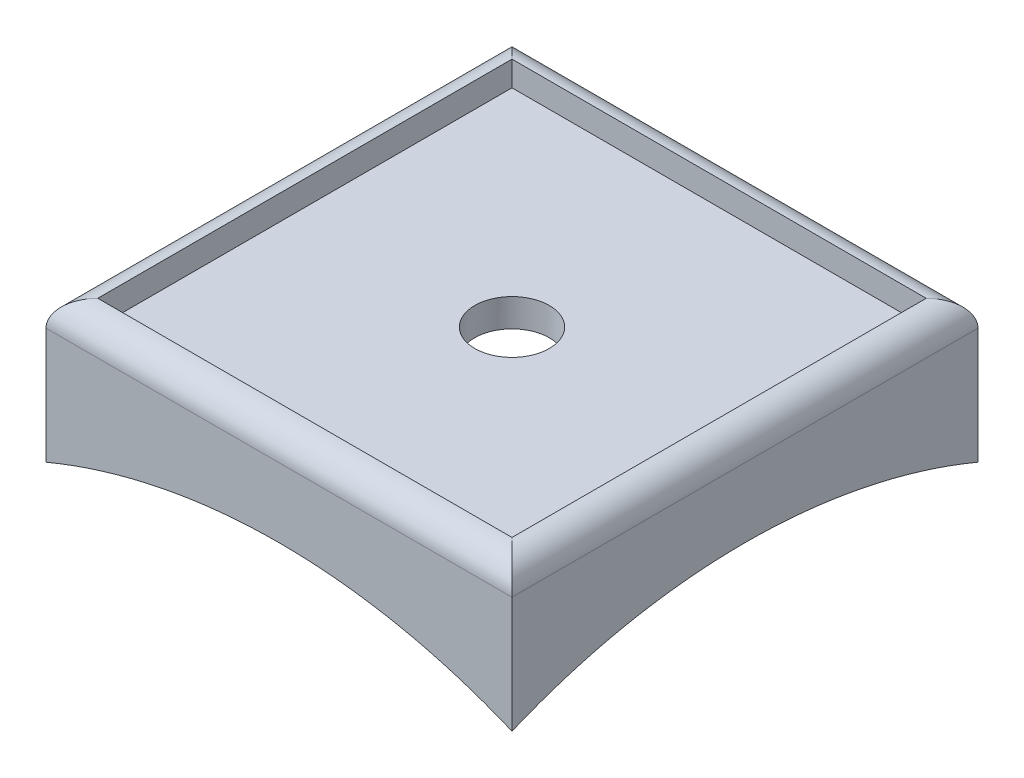
SolidWorks part; units mm, degrees
ref_plane "前视基准面" through (0, 0, 0) normal (0, 0, 1) x (1, 0, 0)
ref_plane "上视基准面" through (0, 0, 0) normal (0, 1, 0) x (1, 0, 0)
ref_plane "右视基准面" through (0, 0, 0) normal (1, 0, 0) x (0, 0, -1)
sketch "草图1" plane through (0, 0, 0) normal (0, 0, 1) x (1, 0, 0)
  line L1 (-27, 27) -> (27, 27)
  line L2 (-27, 27) -> (-27, -27)
  line L3 (-27, -27) -> (27, -27)
  line L4 (27, 27) -> (27, -27)
  line L5 (-27, 27) -> (27, -27) construction
  line L6 (-27, -27) -> (27, 27) construction
  point P0 (0, 0)
  dimension "D1" = 54
  dimension "D2" = 54
extrude "凸台-拉伸1" add sketch "草图1" along normal mid plane 54
ref_plane "基准面1" through (0, 27, 0) normal (0, 1, 0) x (1, 0, 0)
sketch "草图2" plane through (0, 27, 0) normal (0, 1, 0) x (1, 0, 0)
  line L1 (-9, 9) -> (9, 9)
  line L2 (-9, 9) -> (-9, -9)
  line L3 (-9, -9) -> (9, -9)
  line L4 (9, 9) -> (9, -9)
  line L5 (-9, 9) -> (9, -9) construction
  line L6 (-9, -9) -> (9, 9) construction
  line L7 (-27, -27) -> (27, -27)
  line L8 (-27, -27) -> (-27, 27)
  line L9 (-27, 27) -> (27, 27)
  line L10 (27, -27) -> (27, 27)
  line L11 (-27, -27) -> (27, 27) construction
  line L12 (-27, 27) -> (27, -27) construction
  point P0 (0, 0)
  point P6 (0, 0)
  dimension "D1" = 18
  dimension "D2" = 18
extrude "切除-拉伸1" cut sketch "草图2" against normal blind 54
ref_plane "基准面2" through (0, 0, 9) normal (0, 0, 1) x (1, 0, 0)
sketch "草图3" plane through (0, 0, 9) normal (0, 0, 1) x (1, 0, 0)
  line L0 (9, -27) -> (9, 27) construction
  line L1 (-9, -27) -> (9, -27)
  line L2 (-9, -27) -> (-9, 9)
  line L3 (-9, 9) -> (9, 9)
  line L4 (9, -27) -> (9, 9)
  line L5 (9.9, 27) -> (-9.9, 27) construction
  dimension "D1" = 18
extrude "切除-拉伸2" cut sketch "草图3" against normal through all
sketch "草图4" plane through (0, 0, 0) normal (0, 0, 1) x (1, 0, 0)
  line L0 (0, 25) -> (0, -25)
  arc A0 (0, 25) -> (0, -25) centre (0, 0) ccw
  dimension "D1" = 50
revolve "切除-旋转1" cut sketch "草图4" angle 360 about L0
fillet "圆角1" radius 1 4 edges at (-9, 27, 0) (0, 27, -9) (9, 27, 0) (0, 27, 9)
scale "缩放比例1" scale about origin uniform scaling yes scale factor 2.083333
ref_plane "基准面3" through (0, 56.25, 0) normal (0, 1, 0) x (1, 0, 0)
sketch "草图5" plane through (0, 56.25, 0) normal (0, 1, 0) x (1, 0, 0)
  line L1 (-16.6667, 16.6667) -> (16.6667, 16.6667)
  line L2 (-16.6667, 16.6667) -> (-16.6667, -16.6667)
  line L3 (-16.6667, -16.6667) -> (16.6667, -16.6667)
  line L4 (16.6667, 16.6667) -> (16.6667, -16.6667)
  line L5 (-16.6667, 16.6667) -> (16.6667, -16.6667) construction
  line L6 (-16.6667, -16.6667) -> (16.6667, 16.6667) construction
  point P0 (0, 0)
extrude "切除-拉伸3" cut sketch "草图5" against normal blind 2
ref_plane "基准面4" through (0, 54.25, 0) normal (0, 1, 0) x (1, 0, 0)
sketch "草图6" plane through (0, 54.25, 0) normal (0, 1, 0) x (1, 0, 0)
  circle A0 centre (0, 0) radius 3
  dimension "D1" = 6
extrude "切除-拉伸4" cut sketch "草图6" against normal blind 6
